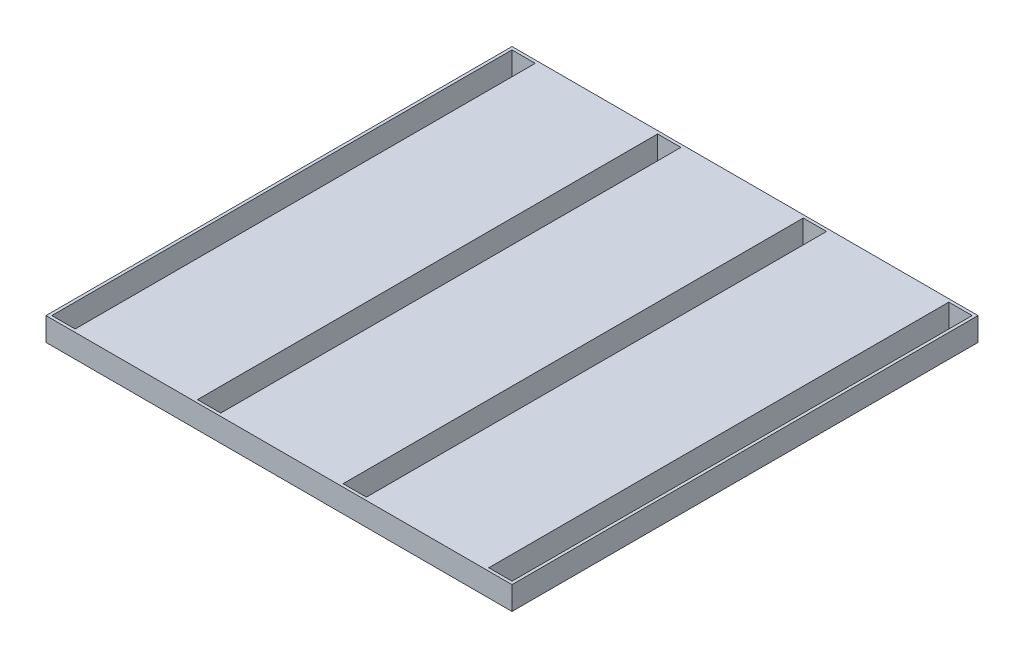
SolidWorks part; units mm, degrees
ref_plane "Front Plane" through (0, 0, 0) normal (0, 0, 1) x (1, 0, 0)
ref_plane "Top Plane" through (0, 0, 0) normal (0, 1, 0) x (1, 0, 0)
ref_plane "Right Plane" through (0, 0, 0) normal (1, 0, 0) x (0, 0, -1)
sketch "Sketch1" plane through (0, 0, 0) normal (0, 1, 0) x (1, 0, 0)
  line L0 (12.75, -0.25) -> (12.75, -39.75)
  line L1 (0, 0) -> (40, 0)
  line L2 (0, 0) -> (0, -40)
  line L3 (0, -40) -> (40, -40)
  line L4 (40, 0) -> (40, -40)
  line L5 (0.25, -0.25) -> (2.25, -0.25)
  line L6 (0.25, -0.25) -> (0.25, -39.75)
  line L7 (0.25, -39.75) -> (2.25, -39.75)
  line L8 (2.25, -0.25) -> (2.25, -39.75)
  line L9 (12.75, -0.25) -> (14.75, -0.25)
  line L10 (14.75, -0.25) -> (14.75, -39.75)
  line L11 (12.75, -39.75) -> (14.75, -39.75)
  line L12 (25.25, -0.25) -> (25.25, -39.75)
  line L13 (25.25, -0.25) -> (27.25, -0.25)
  line L14 (27.25, -0.25) -> (27.25, -39.75)
  line L15 (25.25, -39.75) -> (27.25, -39.75)
  line L16 (37.75, -0.25) -> (37.75, -39.75)
  line L17 (37.75, -0.25) -> (39.75, -0.25)
  line L18 (39.75, -0.25) -> (39.75, -39.75)
  line L19 (37.75, -39.75) -> (39.75, -39.75)
  dimension "D1" = 40
  dimension "D2" = 40
  dimension "D3" = 0.25
  dimension "D4" = 0.25
  dimension "D5" = 0.25
  dimension "D6" = 2
  dimension "D7" = 4
extrude "Boss-Extrude4" add sketch "Sketch1" along normal blind 2
